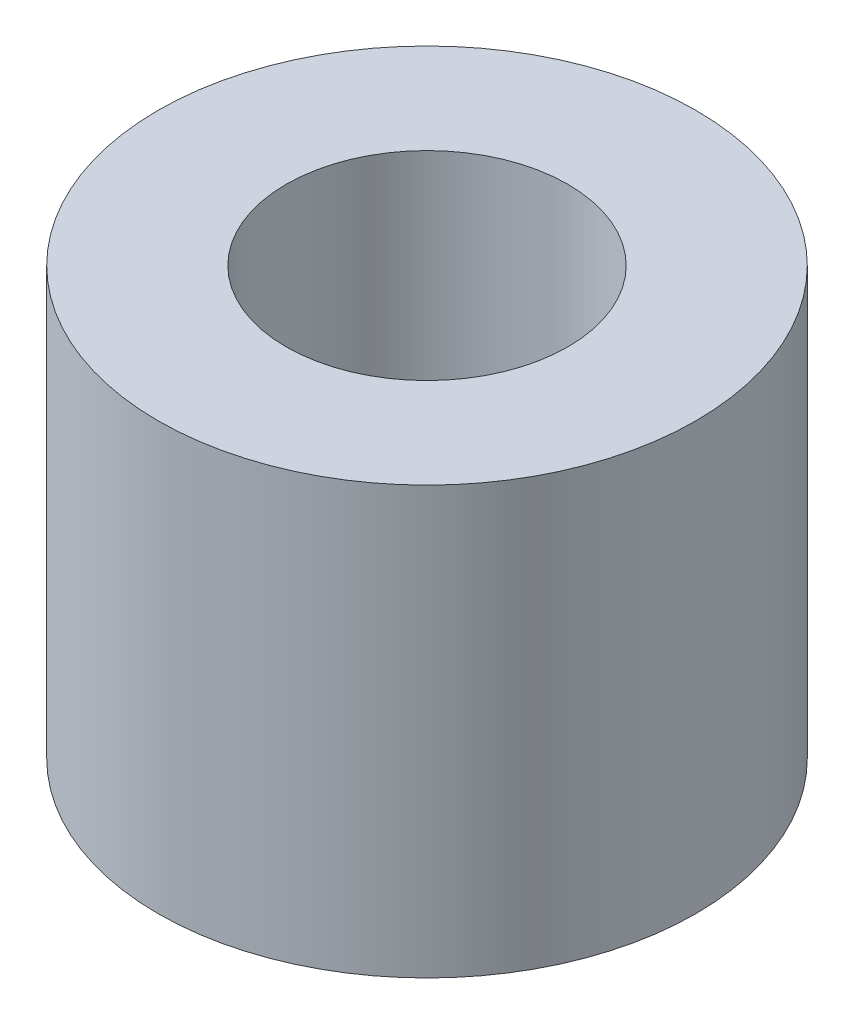
SolidWorks part; units mm, degrees
ref_plane "Alzado" through (0, 0, 0) normal (0, 0, 1) x (1, 0, 0)
ref_plane "Planta" through (0, 0, 0) normal (0, 1, 0) x (1, 0, 0)
ref_plane "Vista lateral" through (0, 0, 0) normal (1, 0, 0) x (0, 0, -1)
sketch "Croquis1" plane through (0, 0, 0) normal (0, 1, 0) x (1, 0, 0)
  circle A0 centre (0, 0) radius 3.3
  circle A2 centre (0, 0) radius 6.3
  dimension "D1" = 6.6
  dimension "D2" = 3
extrude "Saliente-Extruir1" add sketch "Croquis1" along normal mid plane 10
